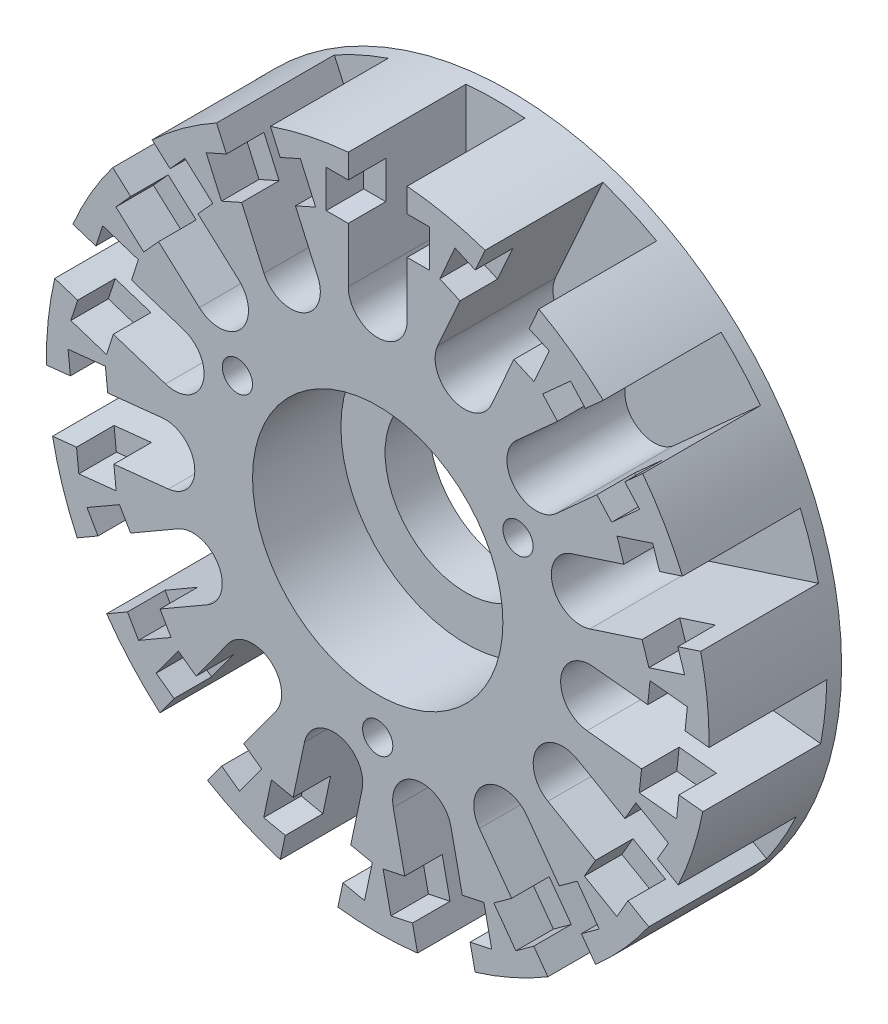
SolidWorks part; units mm, degrees
material "6061 Alloy"
ref_plane "Front Plane" through (0, 0, 0) normal (0, 0, 1) x (1, 0, 0)
ref_plane "Top Plane" through (0, 0, 0) normal (0, 1, 0) x (1, 0, 0)
ref_plane "Right Plane" through (0, 0, 0) normal (1, 0, 0) x (0, 0, -1)
sketch "Sketch1" plane through (0, 0, 0) normal (0, 1, 0) x (1, 0, 0)
  line L0 (22.5, 0) -> (0, 0)
  line L1 (0, 0) -> (0, -9)
  line L2 (0, -9) -> (22.5, -9)
  line L3 (22.5, -9) -> (22.5, 0)
  line L4 (0, 0) -> (0, -9) construction
revolve "Revolve1" add sketch "Sketch1" angle 360 about L4
sketch "Sketch2" plane through (0, 0, 9) normal (0, 0, 1) x (1, 0, 0)
  line L0 (-2, 22.4109) -> (-2, 14.5)
  line L1 (2, 14.5) -> (2, 22.4109)
  arc A0 (-2, 14.5) -> (2, 14.5) centre (0, 14.5) ccw
  arc A1 (2, 22.4109) -> (-2, 22.4109) centre (0, 0) ccw
  dimension "D1" = 14.5
  dimension "D2" = 4
extrude "Cut-Extrude1" cut sketch "Sketch2" against normal blind 8
sketch "Sketch3" plane through (2, 0, 0) normal (-1, 0, 0) x (0, 0, 1)
  line L0 (9, 20.775) -> (6.45, 20.775)
  line L1 (6.45, 20.775) -> (6.45, 18.225)
  line L2 (6.45, 18.225) -> (9, 18.225)
  line L3 (9, 18.225) -> (9, 20.775)
  line L5 (9, -22.5) -> (9, 22.4109) construction
  line L6 (1, 0) -> (9, 0) construction
  dimension "D1" = 2.55
  dimension "D2" = 0
  dimension "D3" = 2.55
  dimension "D4" = 18.225
extrude "Cut-Extrude2" cut sketch "Sketch3" against normal blind 1.5
sketch "Sketch4" plane through (-2, 0, 0) normal (1, 0, 0) x (0, 0, -1)
  line L0 (-9, 18.225) -> (-6.45, 18.225)
  line L1 (-6.45, 18.225) -> (-6.45, 20.775)
  line L2 (-6.45, 20.775) -> (-9, 20.775)
  line L3 (-9, 20.775) -> (-9, 18.225)
  line L5 (-1, 0) -> (-9, 0) construction
  dimension "D1" = 18.225
  dimension "D2" = 2.55
  dimension "D3" = 2.55
extrude "Cut-Extrude3" cut sketch "Sketch4" against normal blind 1.5
hole_wizard "M2.5x0.45 Tapped Hole1" positions "Sketch48" profile "Sketch47" tap size "M2.5x0.45" standard "ANSI Metric"
sketch "Sketch48" plane through (0, 0, 9) normal (0, 0, 1) x (1, 0, 0)
  point P0 (9.5263, 5.5)
  point P1 (0, -11)
  point P2 (-9.5263, 5.5)
sketch "Sketch47" plane through (9.5263, 5.5, 9) normal (1, 0, 0) x (0, -1, 0)
  line L0 (0, 0) -> (0, 6.6159)
  line L1 (0, 6.6159) -> (1.025, 6)
  line L2 (1.025, 6) -> (1.025, 0)
  line L5 (1.025, 0) -> (0, 0)
  line L10 (0, 6.6159) -> (-1.025, 6) construction
  line L11 (0, -6.35) -> (0, 107.95) construction
  dimension "Tap Drill Dia." = 2.05
  dimension "Tap Drill Depth" = 6
  dimension "Drill Angle" = 118
hole_wizard "CBORE for M12 Hex Head Bolt1" positions "Sketch50" profile "Sketch49" counterbore size "M12" standard "ANSI Metric" end condition through all
sketch "Sketch50" plane through (0, 0, 9) normal (0, 0, 1) x (1, 0, 0)
  point P0 (0, 0)
sketch "Sketch49" plane through (0, 0, 9) normal (1, 0, 0) x (0, -1, 0)
  line L0 (0, 0) -> (0, 9)
  line L1 (0, 9) -> (5.5, 9)
  line L3 (5.5, 9) -> (5.5, 6)
  line L4 (5.5, 6) -> (8.5, 6)
  line L5 (8.5, 6) -> (8.5, 0)
  line L7 (8.5, 0) -> (0, 0)
  line L11 (0, -6.35) -> (0, 107.95) construction
  dimension "Thru Hole Dia." = 11
  dimension "Thru Hole Depth" = 9
  dimension "C'Bore Dia." = 17
  dimension "C'Bore Depth" = 6
hole_wizard "M3x0.5 Tapped Hole1" positions "Sketch52" profile "Sketch51" tap size "M3x0.5" standard "ANSI Metric"
sketch "Sketch52" plane through (0, 0, 0) normal (0, 0, -1) x (-1, 0, 0)
  point P0 (16.8875, 9.75)
  point P1 (-16.8875, 9.75)
  point P2 (0, -19.5)
sketch "Sketch51" plane through (-16.8875, 9.75, 0) normal (1, 0, 0) x (0, 1, 0)
  line L0 (0, 0) -> (0, 5.7511)
  line L1 (0, 5.7511) -> (1.25, 5)
  line L2 (1.25, 5) -> (1.25, 0)
  line L5 (1.25, 0) -> (0, 0)
  line L10 (0, 5.7511) -> (-1.25, 5) construction
  line L11 (0, -6.35) -> (0, 107.95) construction
  dimension "Tap Drill Dia." = 2.5
  dimension "Tap Drill Depth" = 5
  dimension "Drill Angle" = 118
pattern_circular "CirPattern1" count 15 over 360 about axis through (0, 0, 0) along (0, 0, 1) of "Cut-Extrude1", "Cut-Extrude3", "Cut-Extrude2"
